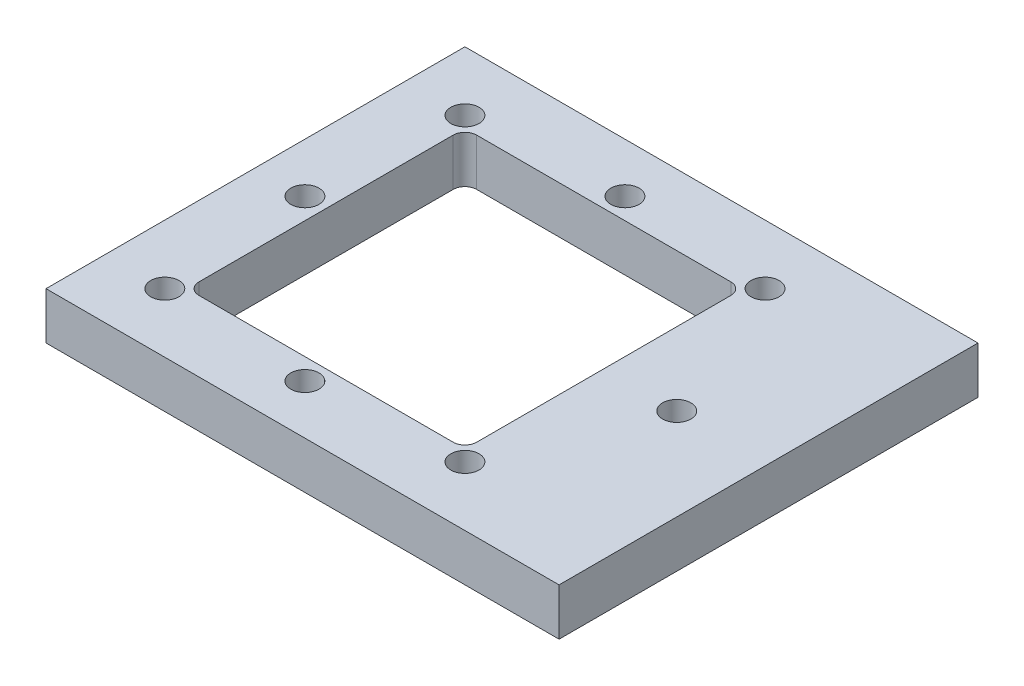
SolidWorks part; units mm, degrees
material "PBT Общее назначение"
ref_plane "Спереди" through (0, 0, 0) normal (0, 0, 1) x (1, 0, 0)
ref_plane "Сверху" through (0, 0, 0) normal (0, 1, 0) x (1, 0, 0)
ref_plane "Справа" through (0, 0, 0) normal (1, 0, 0) x (0, 0, -1)
sketch "Эскиз1" plane through (0, 0, 0) normal (0, 1, 0) x (1, 0, 0)
  line L0 (0, 0) -> (54.5, 0)
  line L1 (0, 0) -> (0, 44.5)
  line L2 (54.5, 0) -> (54.5, 44.5)
  line L3 (0, 44.5) -> (54.5, 44.5)
  dimension "D1" = 44.5
  dimension "D2" = 54.5
extrude "Бобышка-Вытянуть1" add sketch "Эскиз1" along normal blind 5
sketch "Эскиз2" plane through (0, 5, 0) normal (0, 1, 0) x (1, 0, 0)
  line L0 (7.5, 37) -> (37, 37)
  line L1 (7.5, 37) -> (7.5, 7.5)
  line L2 (37, 37) -> (37, 7.5)
  line L3 (7.5, 7.5) -> (37, 7.5)
  line L4 (0, 22.25) -> (54.5, 22.25) construction
  line L5 (0, 44.5) -> (0, 0) construction
  line L6 (54.5, 0) -> (54.5, 44.5) construction
  point P8 (37, 22.25)
  dimension "D1" = 29.5
  dimension "D2" = 29.5
  dimension "D3" = 7.5
extrude "Вырез-Вытянуть1" cut sketch "Эскиз2" against normal through all
fillet "Скругление1" radius 1.25 4 edges at (37, 2.5, -7.5) (37, 2.5, -37) (7.5, 2.5, -7.5) (7.5, 2.5, -37)
sketch "Эскиз3" plane through (0, 0, 0) normal (0, -1, 0) x (1, 0, 0)
  arc A0 (45.95, -29.6534) -> (45.95, -14.8466) centre (44.75, -22.25) ccw construction
  arc A1 (45.95, -29.6534) -> (45.95, -14.8466) centre (44.75, -22.25) ccw construction
sketch "Эскиз4" plane through (0, 5, 0) normal (0, 1, 0) x (1, 0, 0)
  arc A0 (45.95, 14.8466) -> (45.95, 29.6534) centre (44.75, 22.25) ccw construction
  arc A1 (45.95, 14.8466) -> (45.95, 29.6534) centre (44.75, 22.25) ccw construction
  circle A2 centre (44.75, 22.25) radius 1.5
  dimension "D1" = 3
extrude "Вырез-Вытянуть2" cut sketch "Эскиз4" against normal through all
sketch "Эскиз6" plane through (0, 5, 0) normal (0, 1, 0) x (1, 0, 0)
  line L0 (44.75, 22.25) -> (46.25, 22.25) construction
  circle A0 centre (44.75, 22.25) radius 1.5 construction
ref_plane "Плоскость1" through (0, 0, -22.25) normal (0, 0, 1) x (1, 0, 0)
sketch "Эскиз7" plane through (0, 0, 0) normal (0, -1, 0) x (1, 0, 0)
  line L0 (5.25, -39.25) -> (39.25, -39.25) construction
  line L1 (5.25, -39.25) -> (5.25, -5.25) construction
  line L2 (39.25, -39.25) -> (39.25, -5.25) construction
  line L3 (5.25, -5.25) -> (39.25, -5.25) construction
  line L4 (5.25, -39.25) -> (39.25, -5.25) construction
  line L5 (39.25, -39.25) -> (5.25, -5.25) construction
  line L24 (41.75, -8.75) -> (41.75, -9.911) construction
  line L25 (41.75, -8.75) -> (41.75, -9.911) construction
  line L26 (8.75, -2.75) -> (35.75, -2.75) construction
  line L27 (8.75, -2.75) -> (35.75, -2.75) construction
  line L28 (2.75, -35.75) -> (2.75, -8.75) construction
  line L29 (2.75, -35.75) -> (2.75, -8.75) construction
  line L30 (2.75, -22.25) -> (44.75, -22.25) construction
  line L31 (44.75, -22.25) -> (54.5, -22.25) construction
  line L32 (54.5, 0) -> (54.5, -44.5) construction
  line L33 (8.75, -41.75) -> (35.75, -41.75) construction
  line L34 (41.75, -35.75) -> (41.75, -34.589) construction
  line L35 (22.25, -41.75) -> (22.25, -2.75) construction
  circle A0 centre (6.3107, -38.1893) radius 1.5
  circle A1 centre (38.1893, -38.1893) radius 1.5
  circle A2 centre (6.3107, -6.3107) radius 1.5
  circle A3 centre (38.1893, -6.3107) radius 1.5
  arc A9 (41.75, -9.911) -> (45.95, -14.8466) centre (46.75, -9.911) ccw construction
  arc A10 (41.75, -9.911) -> (45.95, -14.8466) centre (46.75, -9.911) ccw construction
  arc A11 (45.95, -29.6534) -> (45.95, -14.8466) centre (44.75, -22.25) ccw construction
  arc A12 (45.95, -29.6534) -> (45.95, -14.8466) centre (44.75, -22.25) ccw construction
  arc A13 (41.75, -8.75) -> (35.75, -2.75) centre (35.75, -8.75) ccw construction
  arc A14 (41.75, -8.75) -> (35.75, -2.75) centre (35.75, -8.75) ccw construction
  arc A15 (8.75, -2.75) -> (2.75, -8.75) centre (8.75, -8.75) ccw construction
  arc A16 (8.75, -2.75) -> (2.75, -8.75) centre (8.75, -8.75) ccw construction
  arc A17 (8.75, -41.75) -> (2.75, -35.75) centre (8.75, -35.75) cw construction
  arc A18 (41.75, -35.75) -> (35.75, -41.75) centre (35.75, -35.75) cw construction
  arc A19 (41.75, -34.589) -> (45.95, -29.6534) centre (46.75, -34.589) cw construction
  circle A20 centre (22.25, -39.25) radius 1.5
  circle A21 centre (5.25, -22.25) radius 1.5
  circle A22 centre (22.25, -5.25) radius 1.5
  dimension "D1" = 3
  dimension "D3" = 2.5
  dimension "D4" = 3
  dimension "D5" = 1.5
  dimension "D6" = 3
  dimension "D2" = 2.5
  dimension "D7" = 1.5
  dimension "D8" = 1.5
  dimension "D9" = 1.5
extrude "Вырез-Вытянуть3" cut sketch "Эскиз7" against normal through all
